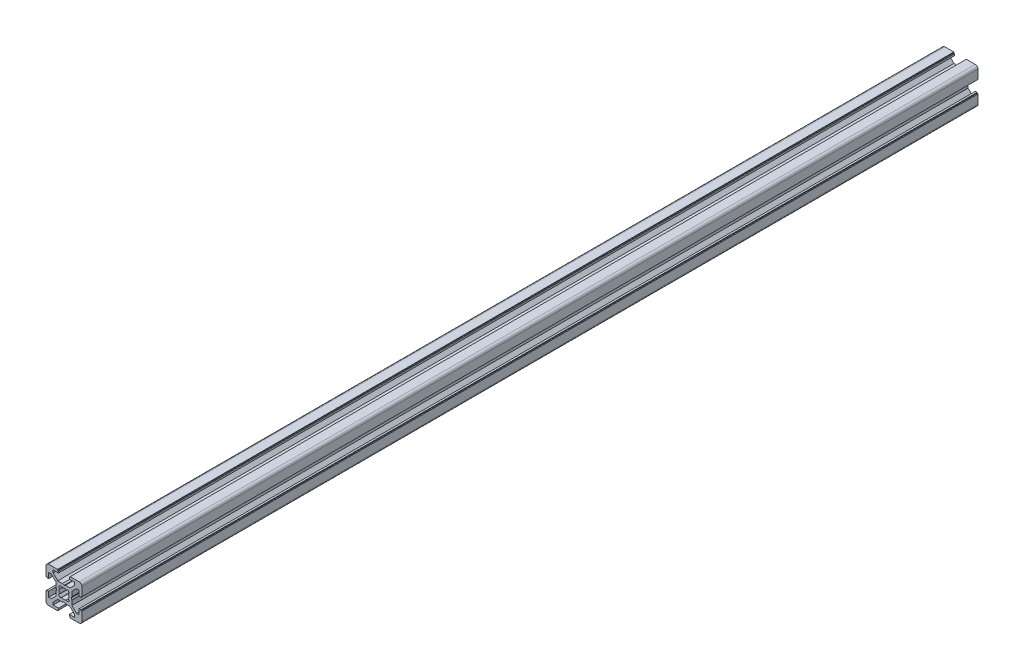
SolidWorks part; units mm, degrees
material "Alliage 1060"
ref_plane "Plan de face" through (0, 0, 0) normal (0, 0, 1) x (1, 0, 0)
ref_plane "Plan de dessus" through (0, 0, 0) normal (0, 1, 0) x (1, 0, 0)
ref_plane "Plan de droite" through (0, 0, 0) normal (1, 0, 0) x (0, 0, -1)
sketch "Esquisse1" plane through (0, 0, 0) normal (0, 0, 1) x (1, 0, 0)
  line L0 (0, 0) -> (-4, 0) construction
  line L1 (-4, 0) -> (-4.5, 0.866)
  line L2 (-4, 0) -> (-4.5, -0.866)
  line L15 (-4.5, 0.866) -> (-4.5, 3.4393)
  line L16 (-4.5, 3.4393) -> (-7.0607, 6)
  line L17 (-7.0607, 6) -> (-8.5, 6)
  line L18 (-8.5, 6) -> (-8.5, 3)
  line L19 (-8.5, 3) -> (-9.5, 3)
  line L20 (-9.5, 3) -> (-9.5, 3.5)
  line L21 (-9.5, 3.5) -> (-10, 3.5)
  line L22 (-10, 3.5) -> (-10, 8.5)
  line L23 (0, 0) -> (0, 1.2745) construction
  line L24 (10, -3.5) -> (10, -8.5)
  line L25 (4.5, -3.4393) -> (7.0607, -6)
  line L26 (-9.5, -3.5) -> (-10, -3.5)
  line L27 (-9.5, -3) -> (-9.5, -3.5)
  line L28 (-8.5, -3) -> (-9.5, -3)
  line L29 (-8.5, -6) -> (-8.5, -3)
  line L30 (-7.0607, -6) -> (-8.5, -6)
  line L31 (-4.5, -0.866) -> (-4.5, -3.4393)
  line L32 (-4.5, -3.4393) -> (-7.0607, -6)
  line L33 (-10, -3.5) -> (-10, -8.5)
  line L34 (4.5, -0.866) -> (4.5, -3.4393)
  line L35 (7.0607, -6) -> (8.5, -6)
  line L36 (8.5, -6) -> (8.5, -3)
  line L37 (8.5, -3) -> (9.5, -3)
  line L38 (9.5, -3) -> (9.5, -3.5)
  line L39 (9.5, -3.5) -> (10, -3.5)
  line L40 (10, 3.5) -> (10, 8.5)
  line L41 (9.5, 3.5) -> (10, 3.5)
  line L42 (9.5, 3) -> (9.5, 3.5)
  line L43 (8.5, 3) -> (9.5, 3)
  line L44 (8.5, 6) -> (8.5, 3)
  line L45 (7.0607, 6) -> (8.5, 6)
  line L46 (4.5, 3.4393) -> (7.0607, 6)
  line L47 (4.5, 0.866) -> (4.5, 3.4393)
  line L48 (4, 0) -> (4.5, -0.866)
  line L49 (4, 0) -> (4.5, 0.866)
  line L50 (3.5, 10) -> (8.5, 10)
  line L51 (3.5, 9.5) -> (3.5, 10)
  line L52 (3, 8.5) -> (3, 9.5)
  line L53 (3, 9.5) -> (3.5, 9.5)
  line L54 (6, 8.5) -> (3, 8.5)
  line L55 (6, 7.0607) -> (6, 8.5)
  line L56 (3.4393, 4.5) -> (6, 7.0607)
  line L57 (0.866, 4.5) -> (3.4393, 4.5)
  line L58 (-0.866, 4.5) -> (-3.4393, 4.5)
  line L59 (-3.4393, 4.5) -> (-6, 7.0607)
  line L60 (-6, 7.0607) -> (-6, 8.5)
  line L61 (-6, 8.5) -> (-3, 8.5)
  line L62 (-3, 8.5) -> (-3, 9.5)
  line L63 (-3, 9.5) -> (-3.5, 9.5)
  line L64 (-3.5, 9.5) -> (-3.5, 10)
  line L65 (-3.5, 10) -> (-8.5, 10)
  line L67 (9.5, -3.5) -> (10, -3.5)
  line L68 (8.5, -3) -> (9.5, -3)
  line L69 (9.5, -3) -> (9.5, -3.5)
  line L70 (8.5, -6) -> (8.5, -3)
  line L71 (7.0607, -6) -> (8.5, -6)
  line L72 (4.5, -3.4393) -> (7.0607, -6)
  line L73 (4.5, -0.866) -> (4.5, -3.4393)
  line L74 (4.5, 0.866) -> (4.5, 3.4393)
  line L75 (4.5, 3.4393) -> (7.0607, 6)
  line L76 (7.0607, 6) -> (8.5, 6)
  line L77 (8.5, 6) -> (8.5, 3)
  line L78 (8.5, 3) -> (9.5, 3)
  line L79 (9.5, 3) -> (9.5, 3.5)
  line L80 (9.5, 3.5) -> (10, 3.5)
  line L82 (-3.5, -10) -> (-8.5, -10)
  line L83 (-3.5, -9.5) -> (-3.5, -10)
  line L84 (-3, -8.5) -> (-3, -9.5)
  line L85 (-3, -9.5) -> (-3.5, -9.5)
  line L86 (-6, -8.5) -> (-3, -8.5)
  line L87 (-6, -7.0607) -> (-6, -8.5)
  line L88 (-3.4393, -4.5) -> (-6, -7.0607)
  line L89 (-0.866, -4.5) -> (-3.4393, -4.5)
  line L90 (0.866, -4.5) -> (3.4393, -4.5)
  line L91 (3.4393, -4.5) -> (6, -7.0607)
  line L92 (6, -7.0607) -> (6, -8.5)
  line L93 (6, -8.5) -> (3, -8.5)
  line L94 (3, -8.5) -> (3, -9.5)
  line L95 (3, -9.5) -> (3.5, -9.5)
  line L96 (3.5, -9.5) -> (3.5, -10)
  line L97 (3.5, -10) -> (8.5, -10)
  line L98 (0, 4) -> (0.866, 4.5)
  line L99 (0, 4) -> (-0.866, 4.5)
  line L100 (4, 0) -> (4.5, -0.866)
  line L101 (4, 0) -> (4.5, 0.866)
  line L102 (0, -4) -> (-0.866, -4.5)
  line L103 (0, -4) -> (0.866, -4.5)
  line L104 (0, 0) -> (-1.9445, 1.9445) construction
  line L105 (10, 3.5) -> (10, 10) [skipped]
  line L106 (10, -3.5) -> (10, -10) [skipped]
  arc A0 (-10, 8.5) -> (-8.5, 10) centre (-8.5, 8.5) cw
  arc A1 (-10, -8.5) -> (-8.5, -10) centre (-8.5, -8.5) ccw
  arc A2 (10, -8.5) -> (8.5, -10) centre (8.5, -8.5) cw
  arc A3 (10, 8.5) -> (8.5, 10) centre (8.5, 8.5) ccw
  circle A4 centre (0, 0) radius 2.75
  point P43 (-10, 10)
  point P98 (0, 0)
  point P101 (-10, -10)
  point P102 (10, -10)
  point P106 (0, 0)
  point P107 (10, 10)
  point P109 (-5.7803, 4.7197)
  dimension "D15" = 1.5
  dimension "D16" = 1.5
  dimension "D14" = 1.5
  dimension "D17" = 5.5
  dimension "D2" = 120
  dimension "D3" = 1
  dimension "D5" = 20
  dimension "D6" = 6
  dimension "D7" = 12
  dimension "D8" = 135
  dimension "D9" = 5.5
  dimension "D10" = 4
  dimension "D11" = 0.5
  dimension "D12" = 4
  dimension "D13" = 0.5
  dimension "D18" = 4
  dimension "D19" = 4.5
  dimension "D4" = 1.5
extrude "Boss.-Extru.1" add sketch "Esquisse1" against normal blind 500 contours L15 L16 L17 L18 L19 L20 L21 L22 A0 L65 L64 L63 L62 L61 L60 L59 L58 L99 L98 L57 L56 L55 L54 L52 L53 L51 L50 A3 L40 L41 L42 L43 L44 L45 L46 L47 L49 L48 L34 L25 L35 L36 L37 L38 L39 L24 A2 L97 L96 L95 L94 L93 L92 L91 L90 L103 L102 L89 L88 L87 L86 L84 L85 L83 L82 A1 L33 L26 L27 L28 L29 L30 L32 L31 L2 L1
sketch "Esquisse2" plane through (0, 0, 0) normal (0, 0, 1) x (1, 0, 0)
  line L0 (1.9496, 3.0009) -> (1.2763, 2.4359)
  line L2 (-3.0009, 1.9496) -> (-2.4359, 1.2763)
  line L3 (-1.9473, 3.0032) -> (-1.2732, 2.4375)
  line L4 (-3.0009, 1.9496) -> (-1.9473, 3.0032)
  line L5 (1.9496, 3.0009) -> (3.0032, 1.9473)
  line L6 (3.0032, 1.9473) -> (2.4375, 1.2732)
  line L7 (3.0009, -1.9496) -> (2.4359, -1.2763)
  line L8 (3.0009, -1.9496) -> (1.9473, -3.0032)
  line L9 (1.9473, -3.0032) -> (1.2732, -2.4375)
  line L10 (-1.9496, -3.0009) -> (-1.2763, -2.4359)
  line L11 (-1.9496, -3.0009) -> (-3.0032, -1.9473)
  line L12 (-3.0032, -1.9473) -> (-2.4375, -1.2732)
  line L13 (0, 0) -> (0.8524, 0) construction
  arc A0 (-2.4359, 1.2763) -> (-2.4375, -1.2732) centre (0, 0) ccw
  arc A1 (1.2763, 2.4359) -> (-1.2732, 2.4375) centre (0, 0) ccw
  arc A2 (2.4359, -1.2763) -> (2.4375, 1.2732) centre (0, 0) ccw
  arc A3 (-1.2763, -2.4359) -> (1.2732, -2.4375) centre (0, 0) ccw
  point P7 (-2.4749, 2.4749)
  point P22 (0, 0)
  dimension "D1" = 5.5
  dimension "D2" = 1.49
  dimension "D3" = 95
  dimension "D4" = 0.8789
  dimension "D5" = 95
  dimension "D6" = 0.88
  dimension "D8" = 45
  dimension "D7" = 4
extrude "Enlèv. mat.-Extru.1" cut sketch "Esquisse2" against normal through all
sketch "Esquisse3" [suppressed] plane through (0, 0, 0) normal (0, 0, 1) x (1, 0, 0)
  line L0 (-3.0009, 1.9496) -> (-2.4359, 1.2763) construction
  line L1 (-2.4375, -1.2732) -> (-3.0032, -1.9473) construction
  line L2 (-3.0032, -1.9473) -> (-1.9496, -3.0009) construction
  line L3 (-1.9496, -3.0009) -> (-1.2763, -2.4359) construction
  line L4 (1.2732, -2.4375) -> (1.9473, -3.0032) construction
  line L5 (1.9473, -3.0032) -> (3.0009, -1.9496) construction
  line L6 (3.0009, -1.9496) -> (2.4359, -1.2763) construction
  line L7 (2.4375, 1.2732) -> (3.0032, 1.9473) construction
  line L8 (3.0032, 1.9473) -> (1.9496, 3.0009) construction
  line L9 (1.9496, 3.0009) -> (1.2763, 2.4359) construction
  line L10 (-1.2732, 2.4375) -> (-1.9473, 3.0032) construction
  line L11 (-1.9473, 3.0032) -> (-3.0009, 1.9496) construction
  line L12 (-3.0009, 1.9496) -> (-2.4359, 1.2763)
  line L13 (-2.4375, -1.2732) -> (-3.0032, -1.9473)
  line L14 (-3.0032, -1.9473) -> (-1.9496, -3.0009)
  line L15 (-1.9496, -3.0009) -> (-1.2763, -2.4359)
  line L16 (1.2732, -2.4375) -> (1.9473, -3.0032)
  line L17 (1.9473, -3.0032) -> (3.0009, -1.9496)
  line L18 (3.0009, -1.9496) -> (2.4359, -1.2763)
  line L19 (2.4375, 1.2732) -> (3.0032, 1.9473)
  line L20 (3.0032, 1.9473) -> (1.9496, 3.0009)
  line L21 (1.9496, 3.0009) -> (1.2763, 2.4359)
  line L22 (-1.2732, 2.4375) -> (-1.9473, 3.0032)
  line L23 (-1.9473, 3.0032) -> (-3.0009, 1.9496)
  line L28 (-10, -3.5) -> (-10, -8.5)
  line L30 (-10, -3.5) -> (-10, -8.5)
  line L32 (-8.5, -10) -> (-3.5, -10)
  line L102 (-8.5, -10) -> (-3.5, -10)
  line L103 (-3.5, -10) -> (-3.5, -9.5)
  line L104 (-3.5, -10) -> (-3.5, -9.5)
  line L105 (-3.5, -9.5) -> (-3, -9.5)
  line L106 (-3.5, -9.5) -> (-3, -9.5)
  line L107 (-3, -9.5) -> (-3, -8.5)
  line L108 (-3, -9.5) -> (-3, -8.5)
  line L109 (-3, -8.5) -> (-6, -8.5)
  line L110 (-3, -8.5) -> (-6, -8.5)
  line L111 (-6, -8.5) -> (-6, -7.0607)
  line L112 (-6, -8.5) -> (-6, -7.0607)
  line L113 (-6, -7.0607) -> (-3.4393, -4.5)
  line L114 (-6, -7.0607) -> (-3.4393, -4.5)
  line L115 (-3.4393, -4.5) -> (-0.866, -4.5)
  line L116 (-3.4393, -4.5) -> (-0.866, -4.5)
  line L117 (-0.866, -4.5) -> (0, -4)
  line L118 (-0.866, -4.5) -> (0, -4)
  line L119 (0, -4) -> (0.866, -4.5)
  line L120 (0, -4) -> (0.866, -4.5)
  line L121 (0.866, -4.5) -> (3.4393, -4.5)
  line L122 (0.866, -4.5) -> (3.4393, -4.5)
  line L123 (3.4393, -4.5) -> (6, -7.0607)
  line L124 (3.4393, -4.5) -> (6, -7.0607)
  line L125 (6, -7.0607) -> (6, -8.5)
  line L126 (6, -7.0607) -> (6, -8.5)
  line L127 (6, -8.5) -> (3, -8.5)
  line L128 (6, -8.5) -> (3, -8.5)
  line L129 (3, -8.5) -> (3, -9.5)
  line L130 (3, -8.5) -> (3, -9.5)
  line L131 (3, -9.5) -> (3.5, -9.5)
  line L132 (3, -9.5) -> (3.5, -9.5)
  line L133 (3.5, -9.5) -> (3.5, -10)
  line L134 (-4.5, 3.4393) -> (-4.5, 0.866)
  line L135 (3.5, -9.5) -> (3.5, -10)
  line L136 (3.5, -10) -> (8.5, -10)
  line L137 (3.5, -10) -> (8.5, -10)
  line L138 (10, -8.5) -> (10, -3.5)
  line L139 (10, -8.5) -> (10, -3.5)
  line L140 (10, -3.5) -> (9.5, -3.5)
  line L141 (10, -3.5) -> (9.5, -3.5)
  line L142 (9.5, -3.5) -> (9.5, -3)
  line L143 (9.5, -3.5) -> (9.5, -3)
  line L206 (-4.5, 3.4393) -> (-4.5, 0.866)
  line L216 (9.5, -3) -> (8.5, -3)
  line L217 (9.5, -3) -> (8.5, -3)
  line L218 (8.5, -3) -> (8.5, -6)
  line L219 (8.5, -3) -> (8.5, -6)
  line L220 (8.5, -6) -> (7.0607, -6)
  line L221 (8.5, -6) -> (7.0607, -6)
  line L222 (7.0607, -6) -> (4.5, -3.4393)
  line L223 (7.0607, -6) -> (4.5, -3.4393)
  line L224 (4.5, -3.4393) -> (4.5, -0.866)
  line L225 (4.5, -3.4393) -> (4.5, -0.866)
  line L226 (4.5, -0.866) -> (4, 0)
  line L227 (4.5, -0.866) -> (4, 0)
  line L228 (4, 0) -> (4.5, 0.866)
  line L229 (4, 0) -> (4.5, 0.866)
  line L230 (4.5, 0.866) -> (4.5, 3.4393)
  line L231 (4.5, 0.866) -> (4.5, 3.4393)
  line L232 (4.5, 3.4393) -> (7.0607, 6)
  line L233 (4.5, 3.4393) -> (7.0607, 6)
  line L234 (7.0607, 6) -> (8.5, 6)
  line L235 (7.0607, 6) -> (8.5, 6)
  line L236 (8.5, 6) -> (8.5, 3)
  line L237 (8.5, 6) -> (8.5, 3)
  line L238 (8.5, 3) -> (9.5, 3)
  line L239 (8.5, 3) -> (9.5, 3)
  line L240 (9.5, 3) -> (9.5, 3.5)
  line L241 (9.5, 3) -> (9.5, 3.5)
  line L242 (9.5, 3.5) -> (10, 3.5)
  line L243 (9.5, 3.5) -> (10, 3.5)
  line L244 (10, 3.5) -> (10, 8.5)
  line L245 (10, 3.5) -> (10, 8.5)
  line L246 (8.5, 10) -> (3.5, 10)
  line L247 (8.5, 10) -> (3.5, 10)
  line L248 (3.5, 10) -> (3.5, 9.5)
  line L249 (3.5, 10) -> (3.5, 9.5)
  line L250 (3.5, 9.5) -> (3, 9.5)
  line L251 (3.5, 9.5) -> (3, 9.5)
  line L252 (3, 9.5) -> (3, 8.5)
  line L253 (3, 9.5) -> (3, 8.5)
  line L254 (3, 8.5) -> (6, 8.5)
  line L255 (3, 8.5) -> (6, 8.5)
  line L256 (6, 8.5) -> (6, 7.0607)
  line L257 (6, 8.5) -> (6, 7.0607)
  line L258 (6, 7.0607) -> (3.4393, 4.5)
  line L259 (6, 7.0607) -> (3.4393, 4.5)
  line L260 (3.4393, 4.5) -> (0.866, 4.5)
  line L261 (3.4393, 4.5) -> (0.866, 4.5)
  line L262 (0.866, 4.5) -> (0, 4)
  line L263 (0.866, 4.5) -> (0, 4)
  line L264 (0, 4) -> (-0.866, 4.5)
  line L265 (0, 4) -> (-0.866, 4.5)
  line L266 (-0.866, 4.5) -> (-3.4393, 4.5)
  line L267 (-0.866, 4.5) -> (-3.4393, 4.5)
  line L268 (-3.4393, 4.5) -> (-6, 7.0607)
  line L269 (-3.4393, 4.5) -> (-6, 7.0607)
  line L270 (-6, 7.0607) -> (-6, 8.5)
  line L271 (-6, 7.0607) -> (-6, 8.5)
  line L272 (-6, 8.5) -> (-3, 8.5)
  line L273 (-6, 8.5) -> (-3, 8.5)
  line L274 (-3, 8.5) -> (-3, 9.5)
  line L275 (-3, 8.5) -> (-3, 9.5)
  line L276 (-3, 9.5) -> (-3.5, 9.5)
  line L277 (-3, 9.5) -> (-3.5, 9.5)
  line L278 (-3.5, 9.5) -> (-3.5, 10)
  line L279 (-3.5, 9.5) -> (-3.5, 10)
  line L280 (-3.5, 10) -> (-8.5, 10)
  line L281 (-3.5, 10) -> (-8.5, 10)
  line L282 (-10, 8.5) -> (-10, 3.5)
  line L283 (-10, 8.5) -> (-10, 3.5)
  line L284 (-10, 3.5) -> (-9.5, 3.5)
  line L285 (-10, 3.5) -> (-9.5, 3.5)
  line L286 (-9.5, 3.5) -> (-9.5, 3)
  line L287 (-9.5, 3.5) -> (-9.5, 3)
  line L288 (-9.5, 3) -> (-8.5, 3)
  line L289 (-9.5, 3) -> (-8.5, 3)
  line L290 (-8.5, 3) -> (-8.5, 6)
  line L291 (-8.5, 3) -> (-8.5, 6)
  line L292 (-8.5, 6) -> (-7.0607, 6)
  line L293 (-8.5, 6) -> (-7.0607, 6)
  line L294 (-7.0607, 6) -> (-4.5, 3.4393)
  line L295 (-7.0607, 6) -> (-4.5, 3.4393)
  line L296 (-4.5, 0.866) -> (-4, 0)
  line L297 (-4.5, 0.866) -> (-4, 0)
  line L298 (-4, 0) -> (-4.5, -0.866)
  line L299 (-4, 0) -> (-4.5, -0.866)
  line L300 (-4.5, -0.866) -> (-4.5, -3.4393)
  line L301 (-4.5, -0.866) -> (-4.5, -3.4393)
  line L302 (-4.5, -3.4393) -> (-7.0607, -6)
  line L303 (-4.5, -3.4393) -> (-7.0607, -6)
  line L304 (-7.0607, -6) -> (-8.5, -6)
  line L305 (-7.0607, -6) -> (-8.5, -6)
  line L306 (-8.5, -6) -> (-8.5, -3)
  line L307 (-8.5, -6) -> (-8.5, -3)
  line L308 (-8.5, -3) -> (-9.5, -3)
  line L309 (-8.5, -3) -> (-9.5, -3)
  line L310 (-9.5, -3) -> (-9.5, -3.5)
  line L311 (-9.5, -3) -> (-9.5, -3.5)
  line L312 (-9.5, -3.5) -> (-10, -3.5)
  line L313 (-9.5, -3.5) -> (-10, -3.5)
  arc A0 (-2.4359, 1.2763) -> (-2.4375, -1.2732) centre (0, 0) ccw construction
  arc A1 (-1.2763, -2.4359) -> (1.2732, -2.4375) centre (0, 0) ccw construction
  arc A2 (2.4359, -1.2763) -> (2.4375, 1.2732) centre (0, 0) ccw construction
  arc A3 (1.2763, 2.4359) -> (-1.2732, 2.4375) centre (0, 0) ccw construction
  arc A4 (-10, -8.5) -> (-8.5, -10) centre (-8.5, -8.5) ccw
  arc A6 (-10, -8.5) -> (-8.5, -10) centre (-8.5, -8.5) ccw
  arc A12 (-2.4359, 1.2763) -> (-2.4375, -1.2732) centre (0, 0) ccw
  arc A13 (-1.2763, -2.4359) -> (1.2732, -2.4375) centre (0, 0) ccw
  arc A14 (2.4359, -1.2763) -> (2.4375, 1.2732) centre (0, 0) ccw
  arc A15 (1.2763, 2.4359) -> (-1.2732, 2.4375) centre (0, 0) ccw
  arc A20 (8.5, -10) -> (10, -8.5) centre (8.5, -8.5) ccw
  arc A22 (8.5, -10) -> (10, -8.5) centre (8.5, -8.5) ccw
  arc A24 (10, 8.5) -> (8.5, 10) centre (8.5, 8.5) ccw
  arc A25 (10, 8.5) -> (8.5, 10) centre (8.5, 8.5) ccw
  arc A26 (-8.5, 10) -> (-10, 8.5) centre (-8.5, 8.5) ccw
  arc A27 (-8.5, 10) -> (-10, 8.5) centre (-8.5, 8.5) ccw
  dimension "D1" = 0
sketch "Esquisse4" [suppressed] plane through (10, 0, 0) normal (1, 0, 0) x (0, 0, -1)
  line L0 (0, 0) -> (400, 0) construction
  circle A0 centre (200, 0) radius 3
  dimension "D1" = 6
extrude "Enlèv. mat.-Extru.2" [suppressed] cut sketch "Esquisse4" against normal through all both and the other way through all
sketch "Esquisse5" [suppressed] plane through (10, 0, 0) normal (1, 0, 0) x (0, 0, -1)
  line L0 (70, 0) -> (0, 0) construction
  line L1 (70, 0) -> (0, 0)
  circle A0 centre (35, 0) radius 3
  dimension "D1" = 6
extrude "Enlèv. mat.-Extru.3" [suppressed] cut sketch "Esquisse5" against normal through all both and the other way through all contours L1 A0 | L1 A0
